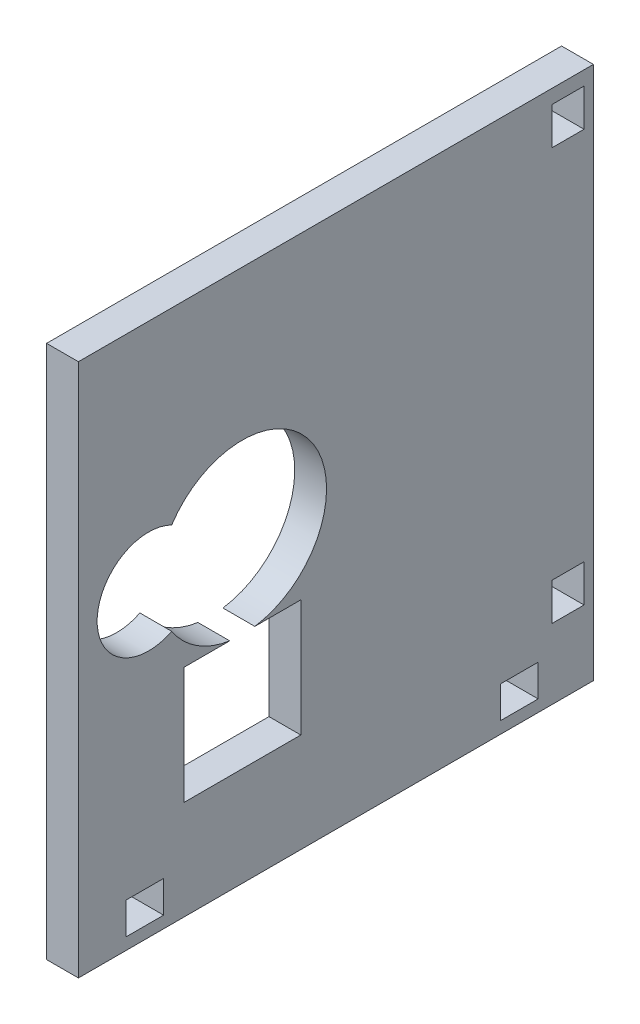
SolidWorks part; units mm, degrees
material "Delrin 2700 NC010, Low Viscosity Acetal Copolymer (SS)"
ref_plane "Front Plane" through (0, 0, 0) normal (0, 0, 1) x (1, 0, 0)
ref_plane "Top Plane" through (0, 0, 0) normal (0, 1, 0) x (1, 0, 0)
ref_plane "Right Plane" through (0, 0, 0) normal (1, 0, 0) x (0, 0, -1)
sketch "Sketch1" plane through (0, 0, 0) normal (1, 0, 0) x (0, 0, -1)
  line L0 (8.89, -988.2652) -> (8.89, 49011.7348) construction
  line L1 (0, 0) -> (27.94, 0)
  line L2 (0, 0) -> (0, 28.956)
  line L3 (0, 28.956) -> (27.94, 28.956)
  line L4 (27.94, 0) -> (27.94, 28.956)
  line L5 (12.065, 5.3848) -> (5.715, 5.3848)
  line L6 (12.065, 5.3848) -> (12.065, 11.7348)
  line L7 (12.065, 11.7348) -> (5.715, 11.7348)
  line L8 (5.715, 5.3848) -> (5.715, 11.7348)
  line L9 (0, 14.478) -> (27.94, 14.478) construction
  line L10 (27.432, 5.842) -> (25.7048, 5.842)
  line L11 (27.432, 28.194) -> (25.7048, 28.194)
  line L12 (27.432, 28.194) -> (27.432, 26.162)
  line L13 (27.432, 26.162) -> (25.7048, 26.162)
  line L14 (25.7048, 28.194) -> (25.7048, 26.162)
  line L15 (27.432, 5.842) -> (27.432, 3.81)
  line L16 (27.432, 3.81) -> (25.7048, 3.81)
  line L17 (25.7048, 5.842) -> (25.7048, 3.81)
  line L18 (27.432, 28.194) -> (27.432, 5.842) construction
  point P25 (8.89, 11.7348)
  dimension "D1" = 27.94
  dimension "D2" = 28.956
  dimension "D3" = 6.35
  dimension "D4" = 6.35
  dimension "D5" = 15.875
  dimension "D6" = 5.3848
  dimension "D7" = 0.762
  dimension "D8" = 2.032
  dimension "D9" = 1.7272
  dimension "D10" = 0.508
  dimension "D11" = 2
  dimension "D12" = 22.352
extrude "Boss-Extrude1" add sketch "Sketch1" along normal blind 1.7272
sketch "Sketch3" plane through (1.7272, 0, 0) normal (1, 0, 0) x (0, 0, -1)
  line L0 (27.94, 0) -> (27.94, 28.956) construction
  line L1 (0, 0) -> (27.94, 0) construction
  line L2 (2.5908, 0.6413) -> (4.6228, 0.6413)
  line L3 (2.5908, 2.3685) -> (2.5908, 0.6413)
  line L4 (4.6228, 2.3685) -> (2.5908, 2.3685)
  line L5 (4.6228, 0.6413) -> (4.6228, 2.3685)
  line L20 (22.9108, 0.6413) -> (24.9428, 0.6413)
  line L21 (22.9108, 2.3685) -> (22.9108, 0.6413)
  line L22 (24.9428, 2.3685) -> (22.9108, 2.3685)
  line L23 (24.9428, 0.6413) -> (24.9428, 2.3685)
  dimension "D1" = 2.032
  dimension "D2" = 1.7272
  dimension "D3" = 2.9972
  dimension "D4" = 0.6413
  dimension "D5" = 2
extrude "Cut-Extrude1" cut sketch "Sketch3" against normal up to surface (1.7272 mm away) up to face at (0, 27.178, -26.5684)
sketch "Sketch4" plane through (1.7272, 0, 0) normal (1, 0, 0) x (0, 0, -1)
  line L0 (8.89, -984.76) -> (8.89, 49015.24) construction
  line L1 (12.065, 11.7348) -> (5.715, 11.7348) construction
  line L2 (12.065, 11.7348) -> (5.715, 11.7348) construction
  circle A0 centre (8.89, 16.256) radius 4.572
  circle A1 centre (3.81, 16.256) radius 2.794
  point P5 (8.89, 11.7348)
  line M20 (5.715, 11.7348) -> (12.065, 11.7348)
  dimension "D1" = 9.144
  dimension "D2" = 5.588
  dimension "D3" = 5.08
  dimension "D4" = 4.5212
extrude "Cut-Extrude4" cut sketch "Sketch4" against normal up to surface (1.7272 mm away) contours A1 A0 M20 | A0 A1 | A0 A1 up to face at (0, 1.5049, -23.9268)
